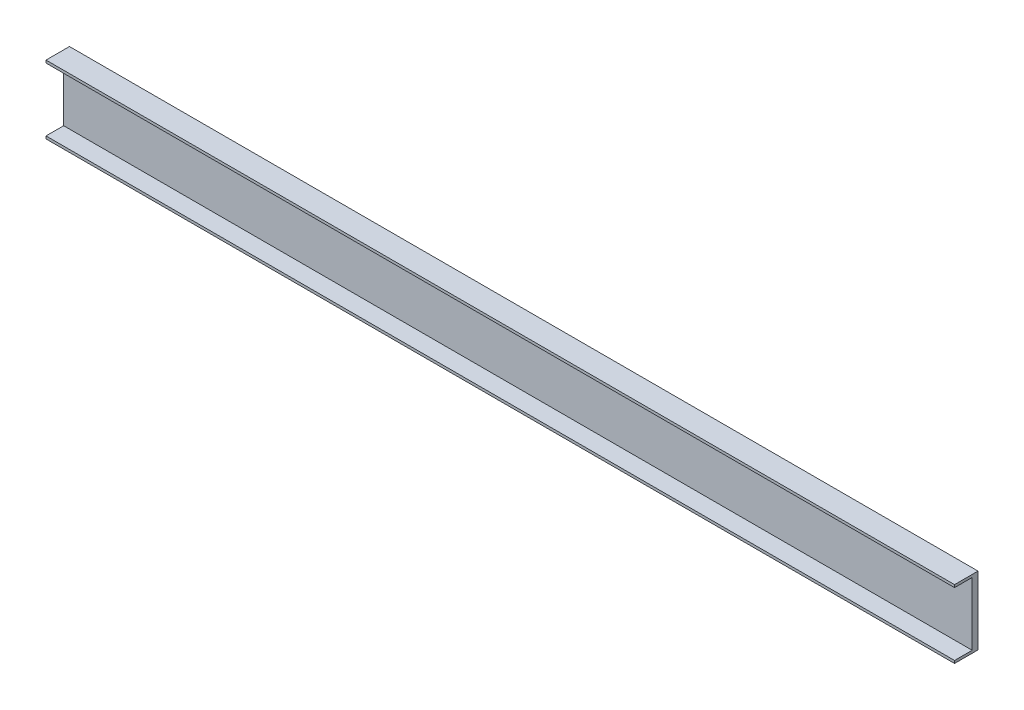
SolidWorks part; units mm, degrees
ref_plane "前视" through (0, 0, 0) normal (0, 0, 1) x (1, 0, 0)
ref_plane "上视" through (0, 0, 0) normal (0, 1, 0) x (1, 0, 0)
ref_plane "右视" through (0, 0, 0) normal (1, 0, 0) x (0, 0, -1)
sketch "草图1" plane through (0, 0, 0) normal (0, 0, 1) x (1, 0, 0)
  line L0 (0, 280.187) -> (0, -298.191) construction
  line L1 (-2057.2074, 0) -> (2116.7847, 0) construction
  line L2 (2116.7847, 80) -> (-2430.1435, 80) construction
  line L3 (-1995, 150) -> (1995, 150)
  line L5 (-1995, -150) -> (1995, -150)
  line L6 (1995, 150) -> (1995, -150)
  line L7 (-2430.1435, -80) -> (2116.7847, -80) construction
  line L8 (1940, 266.4652) -> (1940, -249.2739) construction
  line L9 (1860, -249.2739) -> (1860, 266.4652) construction
  line L10 (1060, 266.4652) -> (1060, -361.7988) construction
  line L11 (1780, 266.4652) -> (1780, -249.2739) construction
  line L12 (1780, -249.2739) -> (1700, -249.2739) construction
  line L13 (1700, -249.2739) -> (1700, 266.4652) construction
  line L14 (1540, 266.4652) -> (1540, -361.7988) construction
  line L15 (1380, 266.4652) -> (1380, -361.7988) construction
  line L16 (1220, -361.7988) -> (1220, 266.4652) construction
  line L17 (980, -361.7988) -> (980, 266.4652) construction
  line L18 (740, -361.7988) -> (740, 464.33) construction
  line L19 (820, 266.4652) -> (820, -361.7988) construction
  line L20 (580, -361.7988) -> (580, 266.4652) construction
  line L21 (420, -361.7988) -> (420, 266.4652) construction
  line L22 (300, -298.191) -> (300, 266.4652) construction
  line L23 (60, 280.187) -> (60, -298.191) construction
  line L24 (140, 280.187) -> (140, -298.191) construction
  line L25 (220, -298.191) -> (220, 280.187) construction
  line L26 (-1995, 150) -> (-1995, -150)
  dimension "D1" = 3990
  dimension "D2" = 300
  dimension "D3" = 70
  dimension "D4" = 80
  dimension "D5" = 55
  dimension "D6" = 80
  dimension "D7" = 80
  dimension "D8" = 80
  dimension "D9" = 455
  dimension "D10" = 160
  dimension "D11" = 160
  dimension "D12" = 160
  dimension "D13" = 80
  dimension "D14" = 160
  dimension "D15" = 80
  dimension "D16" = 160
  dimension "D17" = 160
  dimension "D18" = 120
  dimension "D19" = 60
  dimension "D20" = 80
  dimension "D21" = 80
extrude "基体-拉伸" add sketch "草图1" along normal blind 25.5
sketch "草图2" plane through (0, 0, 25.5) normal (0, 0, 1) x (1, 0, 0)
  line L0 (1995, -150) -> (1995, 150) construction
  line L1 (-1995, 150) -> (1995, 150)
  line L2 (-1995, 150) -> (-1995, 138.5)
  line L3 (-1995, 138.5) -> (1995, 138.5)
  line L4 (1995, 150) -> (1995, 138.5)
  line L5 (0, 0) -> (2507.3409, 0) construction
  line L6 (1995, -150) -> (1995, -138.5)
  line L7 (-1995, -138.5) -> (1995, -138.5)
  line L8 (-1995, -150) -> (-1995, -138.5)
  line L9 (-1995, -150) -> (1995, -150)
  dimension "D1" = 11.5
extrude "凸台-拉伸1" add sketch "草图2" along normal blind 77.5
sketch "草图3" plane through (0, 0, 0) normal (0, 0, -1) x (-1, 0, 0)
  line L0 (0, 0) -> (2381.8358, 0) construction
  line L1 (0, 348.8193) -> (0, -302.4645) construction
  line L2 (1300, 348.8193) -> (1300, -385.903) construction
  line L3 (1995, 150) -> (1995, -150) construction
  line L4 (900, 237.7997) -> (900, -385.903) construction
  line L5 (1265, 115) -> (1335, 115)
  line L6 (1265, 115) -> (1265, -115)
  line L7 (1265, -115) -> (1335, -115)
  line L8 (1335, 115) -> (1335, -115)
  line L9 (865, 115) -> (935, 115)
  line L10 (865, 115) -> (865, -115)
  line L11 (865, -115) -> (935, -115)
  line L12 (935, 115) -> (935, -115)
  line L13 (500, -385.903) -> (500, 237.7997) construction
  line L14 (-1265, 115) -> (-1335, 115)
  line L15 (535, -115) -> (465, -115)
  line L16 (535, -115) -> (535, 115)
  line L17 (535, 115) -> (465, 115)
  line L18 (465, -115) -> (465, 115)
  line L19 (-1335, 115) -> (-1335, -115)
  line L20 (-1265, 115) -> (-1265, -115)
  line L21 (-1265, -115) -> (-1335, -115)
  line L22 (-865, -115) -> (-935, -115)
  line L23 (-935, 115) -> (-935, -115)
  line L24 (-865, 115) -> (-935, 115)
  line L25 (-865, 115) -> (-865, -115)
  line L26 (-535, -115) -> (-535, 115)
  line L27 (-535, -115) -> (-465, -115)
  line L28 (-465, -115) -> (-465, 115)
  line L29 (-535, 115) -> (-465, 115)
  dimension "D1" = 695
  dimension "D2" = 70
  dimension "D3" = 230
  dimension "D4" = 400
  dimension "D5" = 70
  dimension "D6" = 230
  dimension "D7" = 400
  dimension "D8" = 70
  dimension "D9" = 230
extrude "凸台-拉伸2" add sketch "草图3" along normal blind 16
